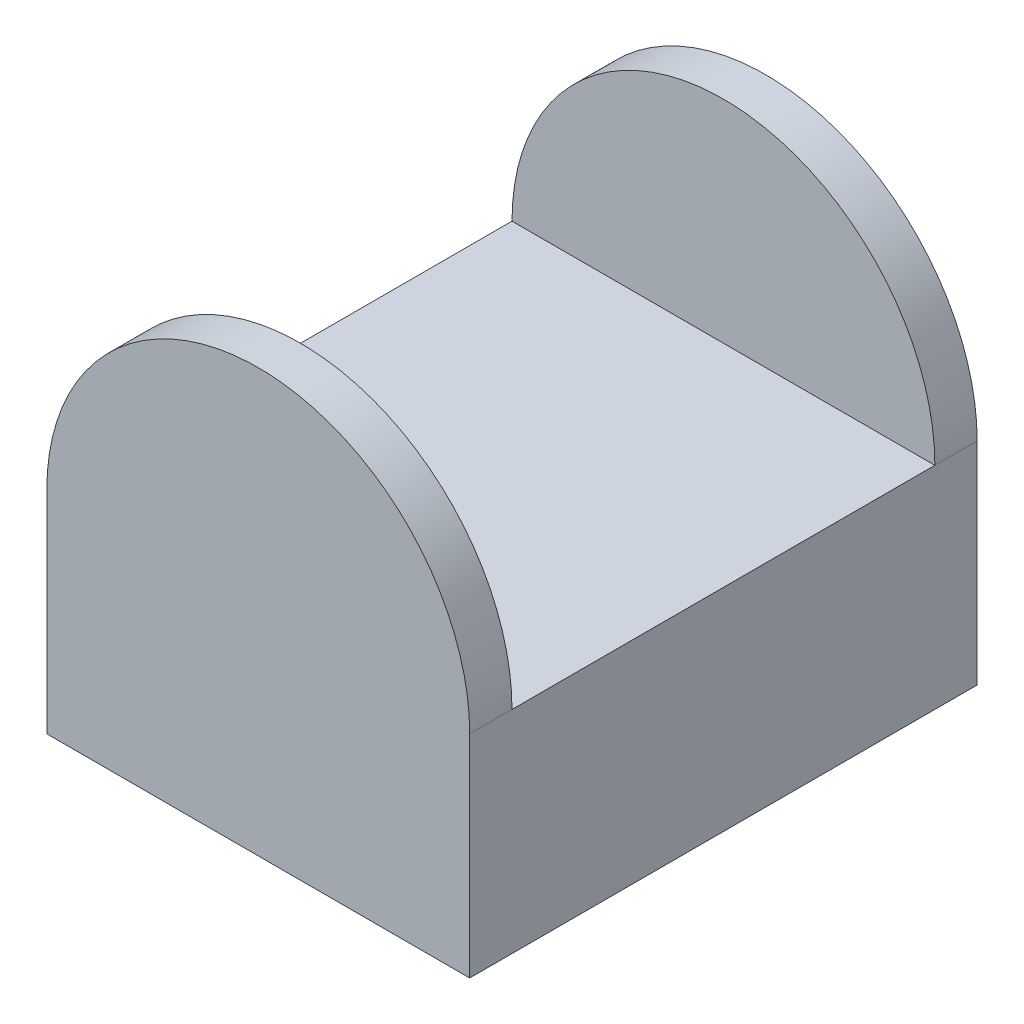
SolidWorks part; units mm, degrees
ref_plane "Front Plane" through (0, 0, 0) normal (0, 0, 1) x (1, 0, 0)
ref_plane "Top Plane" through (0, 0, 0) normal (0, 1, 0) x (1, 0, 0)
ref_plane "Right Plane" through (0, 0, 0) normal (1, 0, 0) x (0, 0, -1)
sketch "Sketch2" plane through (0, 0, 0) normal (0, 0, 1) x (1, 0, 0)
  line L1 (12.7, 0) -> (-12.7, 0) construction
  line L2 (-12.7, 0) -> (-12.7, -12.7)
  line L3 (-12.7, -12.7) -> (12.7, -12.7)
  line L4 (12.7, -12.7) -> (12.7, 0)
  arc A1 (-12.7, 0) -> (12.7, 0) centre (0, 0) cw
  point P4 (0, 0)
  point P9 (0, 12.7)
  point P10 (0, -12.7)
  point P11 (-12.7, 0)
  dimension "D1" = 25.4
  dimension "D2" = 25.4
  dimension "D3" = 12.7
extrude "Boss-Extrude1" add sketch "Sketch2" along normal blind 30.48
sketch "Sketch3" plane through (12.7, 0, 0) normal (1, 0, 0) x (0, 0, -1)
  line L0 (-27.94, 0) -> (-27.94, 12.7)
  line L1 (-30.48, 0) -> (0, 0) construction
  line L2 (0, 12.7) -> (-30.48, 12.7) construction
  line L3 (-27.94, 12.7) -> (-2.54, 12.7)
  line L4 (-2.54, 12.7) -> (-2.54, 0)
  line L5 (-2.54, 0) -> (-27.94, 0)
  line L6 (-30.48, 12.7) -> (-30.48, 0) construction
  line L7 (0, 0) -> (0, 12.7) construction
  dimension "D1" = 2.54
  dimension "D2" = 2.54
extrude "Cut-Extrude1" cut sketch "Sketch3" against normal through all and the other way through all
